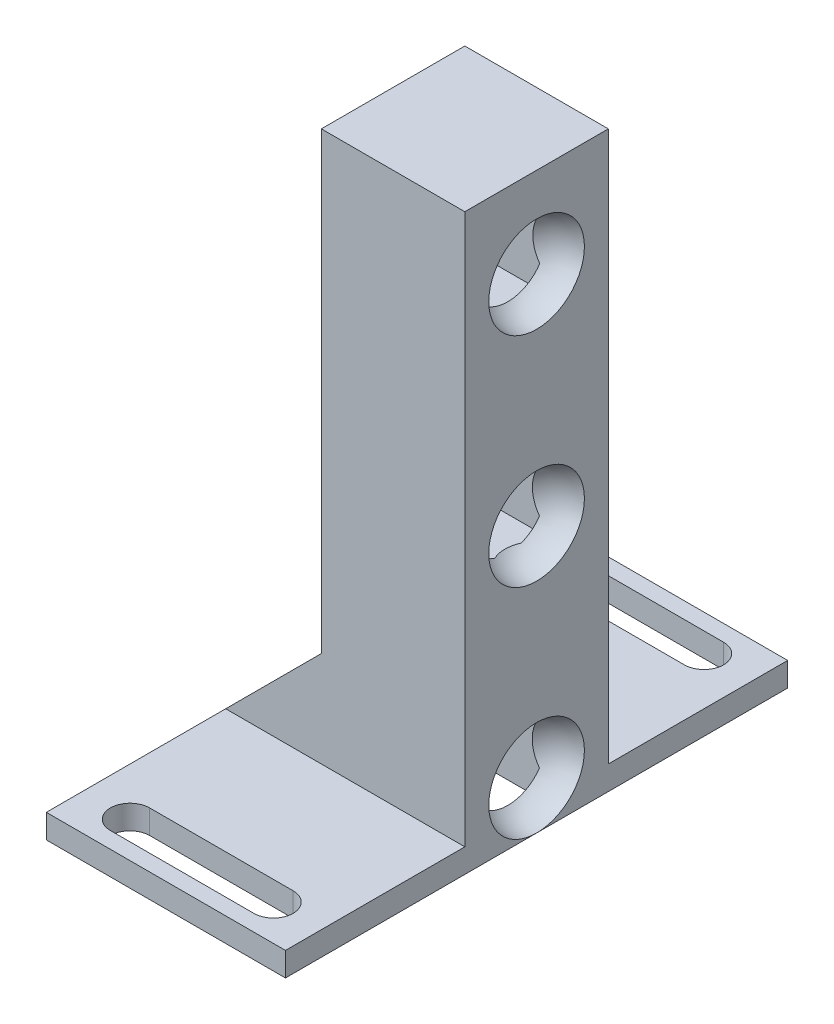
SolidWorks part; units mm, degrees
ref_plane "前视基准面" through (0, 0, 0) normal (0, 0, 1) x (1, 0, 0)
ref_plane "上视基准面" through (0, 0, 0) normal (0, 1, 0) x (1, 0, 0)
ref_plane "右视基准面" through (0, 0, 0) normal (1, 0, 0) x (0, 0, -1)
other "Configuration Table"
sketch "草图1" plane through (0, 0, 0) normal (0, 1, 0) x (1, 0, 0)
  line L1 (-35, 52.5) -> (35, 52.5)
  line L2 (-35, 52.5) -> (-35, -52.5)
  line L3 (-35, -52.5) -> (35, -52.5)
  line L4 (35, 52.5) -> (35, -52.5)
  line L5 (-35, 52.5) -> (35, -52.5) construction
  line L6 (-35, -52.5) -> (35, 52.5) construction
  point P0 (0, 0)
  dimension "D1" = 105
  dimension "D2" = 70
extrude "凸台-拉伸1" add sketch "草图1" along normal blind 5
sketch "草图2" plane through (0, 0, 0) normal (0, 1, 0) x (1, 0, 0)
  line L1 (-15, 15) -> (15, 15)
  line L2 (-15, 15) -> (-15, -15)
  line L3 (-15, -15) -> (15, -15)
  line L4 (15, 15) -> (15, -15)
  line L5 (-15, 15) -> (15, -15) construction
  line L6 (-15, -15) -> (15, 15) construction
  point P0 (0, 0)
  dimension "D1" = 30
  dimension "D2" = 30
extrude "凸台-拉伸2" add sketch "草图2" along normal blind 120
sketch "草图7" plane through (0, 0, 0) normal (0, 0, 1) x (1, 0, 0)
  line L0 (-15, 25) -> (-35, 5)
  line L1 (-15, 120) -> (-15, 5) construction
  line L2 (-35, 5) -> (35, 5) construction
  line L3 (-35, 5) -> (-15, 5)
  line L4 (-15, 5) -> (-15, 25)
  dimension "D1" = 20
  dimension "D2" = 20
extrude "凸台-拉伸3" add sketch "草图7" along normal up to surface and the other way up to surface up to face at (0, 62.5, 15) other way up to face at (0, 62.5, -15)
sketch "草图8" plane through (0, 0, 0) normal (0, 1, 0) x (1, 0, 0)
  line L0 (35, 52.5) -> (-35, 52.5) construction
  line L1 (-35, 52.5) -> (-35, 15) construction
  circle A0 centre (-25, 45) radius 4.1
  dimension "D2" = 8.2
  dimension "D1" = 7.5
  dimension "D3" = 10
extrude "切除-拉伸2" cut sketch "草图8" along normal up to surface (5 mm away) up to face at (-5, 5, 0)
mirror "镜向2" about plane through (0, 0, 0) normal (0, 0, 1) of "切除-拉伸2"
sketch "草图11" plane through (0, 0, 0) normal (0, 1, 0) x (1, 0, 0)
  line L0 (15, 52.5) -> (15, -52.5)
  line L1 (35, 52.5) -> (-35, 52.5) construction
  line L2 (-35, -52.5) -> (35, -52.5) construction
  line L3 (15, -52.5) -> (35, -52.5)
  line L4 (35, -52.5) -> (35, 52.5)
  line L5 (35, 52.5) -> (15, 52.5)
  line L6 (-35, 52.5) -> (-35, 15) construction
  dimension "D1" = 50
extrude "切除-拉伸3" cut sketch "草图11" along normal up to surface (5 mm away) up to face at (-25, 5, 49.1)
sketch "草图12" plane through (0, 0, 0) normal (0, 0, 1) x (1, 0, 0)
  line L0 (15, 120) -> (15, 5) construction
  line L1 (15, 20) -> (15, 0)
  line L2 (-35, 0) -> (15, 0) construction
  arc A0 (15, 20) -> (15, 0) centre (15, 10) ccw
  dimension "D1" = 10
  dimension "D2" = 10
revolve "切除-旋转2" cut sketch "草图12" angle 360 about L1
pattern_linear "阵列(线性)1" count 3 spacing 45.6 along (0, 1, 0) of "切除-旋转2"
sketch "草图14" plane through (0, 0, 0) normal (1, 0, 0) x (0, 0, -1)
  line L5 (-6.5321, 115.9773) -> (6.6679, 115.9773)
  line L6 (-6.5321, 115.9773) -> (-6.5321, 91.9773)
  line L7 (-6.5321, 91.9773) -> (6.6679, 91.9773)
  line L8 (6.6679, 115.9773) -> (6.6679, 91.9773)
  line L9 (-6.5321, 115.9773) -> (6.6679, 91.9773) construction
  line L10 (-6.5321, 91.9773) -> (6.6679, 115.9773) construction
  point P0 (-0.0679, 101.1584)
  dimension "D1" = 13.2
  dimension "D2" = 24
extrude "切除-拉伸4" cut sketch "草图14" against normal through all and the other way blind 9
pattern_linear "阵列(线性)3" count 2 spacing 30 along (1, 0, 0) of "切除-拉伸2"
sketch "草图15" plane through (0, 0, 0) normal (0, 1, 0) x (1, 0, 0)
  line L0 (-25, 49.1) -> (5, 49.1)
  line L1 (5, 49.1) -> (5, 40.9)
  line L2 (5, 40.9) -> (-25, 40.9)
  line L3 (-25, 40.9) -> (-25, 49.1)
  circle A0 centre (-25, 45) radius 4.1 construction
  circle A1 centre (5, 45) radius 4.1 construction
extrude "切除-拉伸5" cut sketch "草图15" along normal up to surface (5 mm away) up to face at (5, 5, -40.9)
mirror "镜向3" about plane through (0, 0, 0) normal (0, 0, 1) of "切除-拉伸5"
mirror "镜向4" about plane through (0, 0, 0) normal (0, 0, 1) of "阵列(线性)3"
sketch "草图17" plane through (0, 0, 0) normal (1, 0, 0) x (0, 0, -1)
  line L0 (52.5, 0) -> (0, 0) construction
  line L1 (-6.6, 18) -> (6.6, 18)
  line L2 (-6.6, 18) -> (-6.6, 0)
  line L3 (-6.6, 0) -> (6.6, 0)
  line L4 (6.6, 18) -> (6.6, 0)
  line L5 (-6.6, 18) -> (6.6, 0) construction
  line L6 (-6.6, 0) -> (6.6, 18) construction
  point P0 (0, 9)
  dimension "D1" = 13.2
  dimension "D2" = 18
extrude "切除-拉伸6" cut sketch "草图17" against normal up to surface and the other way blind 9 up to face at (-25, 15, 0)
sketch "草图18" plane through (0, 0, 0) normal (1, 0, 0) x (0, 0, -1)
  line L1 (-6.5856, 63.1) -> (6.6144, 63.1)
  line L2 (-6.5856, 63.1) -> (-6.5856, 48.1)
  line L3 (-6.5856, 48.1) -> (6.6144, 48.1)
  line L4 (6.6144, 63.1) -> (6.6144, 48.1)
  line L5 (-6.5856, 63.1) -> (6.6144, 48.1) construction
  line L6 (-6.5856, 48.1) -> (6.6144, 63.1) construction
  circle A0 centre (0, 55.6) radius 10 construction
  point P0 (0.0144, 55.6)
  dimension "D1" = 13.2
  dimension "D2" = 15
extrude "切除-拉伸7" cut sketch "草图18" against normal up to surface (15 mm away) and the other way blind 9 up to face at (-15, 72.5, 0)
